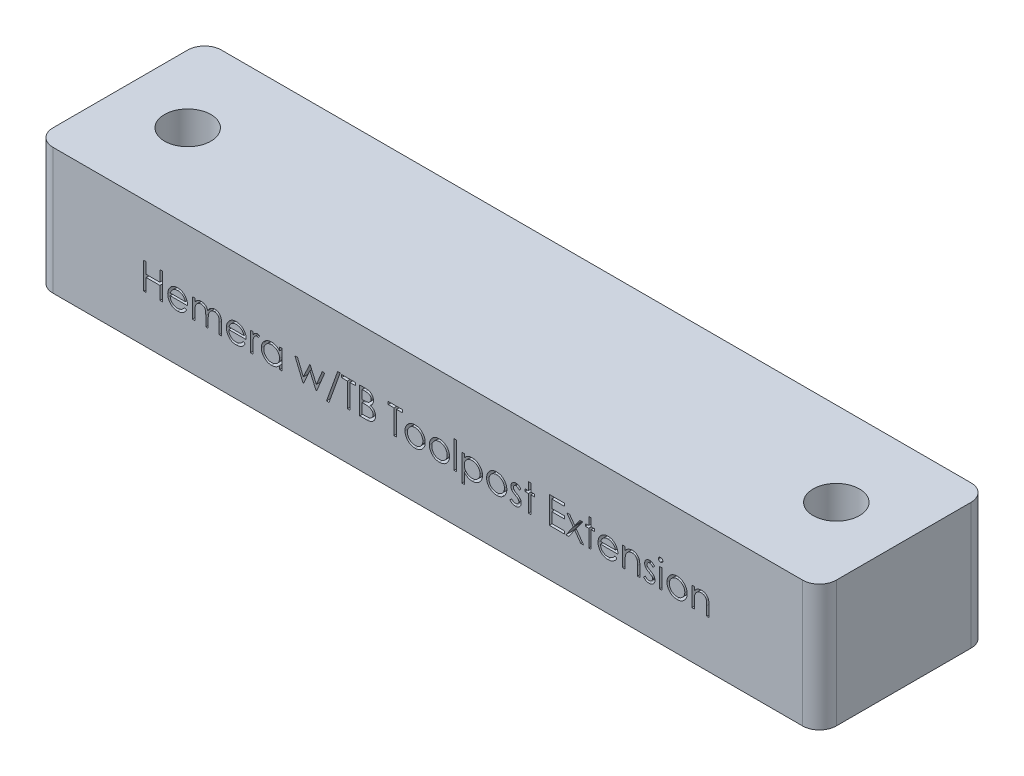
SolidWorks part; units mm, degrees
ref_plane "Front Plane" through (0, 0, 0) normal (0, 0, 1) x (1, 0, 0)
ref_plane "Top Plane" through (0, 0, 0) normal (0, 1, 0) x (1, 0, 0)
ref_plane "Right Plane" through (0, 0, 0) normal (1, 0, 0) x (0, 0, -1)
sketch "Sketch1" plane through (0, 0, 0) normal (0, 1, 0) x (1, 0, 0)
  line L0 (-44.5, -10) -> (44.5, -10)
  line L1 (46.5, -8) -> (46.5, 8)
  line L2 (44.5, 10) -> (-44.5, 10)
  line L3 (-46.5, 8) -> (-46.5, -8)
  arc A0 (44.5, -10) -> (46.5, -8) centre (44.5, -8) ccw
  arc A1 (46.5, 8) -> (44.5, 10) centre (44.5, 8) ccw
  arc A2 (-44.5, 10) -> (-46.5, 8) centre (-44.5, 8) ccw
  arc A3 (-46.5, -8) -> (-44.5, -10) centre (-44.5, -8) ccw
extrude "Boss-Extrude1" add sketch "Sketch1" along normal blind 15
hole_wizard "M5 Clearance Hole1" positions "Sketch2" profile "Sketch3" hole size "M5" standard "ANSI Metric" end condition through all
sketch "Sketch2" plane through (0, 15, 0) normal (0, 1, 0) x (1, 0, 0)
  line L0 (-44.5, -10) -> (44.5, -10) construction
  line L1 (46.5, -8) -> (46.5, 8) construction
  point P0 (38.5, 0)
  point P2 (-38.5, 0)
  dimension "D1" = 77
  dimension "D2" = 10
  dimension "D3" = 8
sketch "Sketch3" plane through (38.5, 15, 0) normal (1, 0, 0) x (0, 0, 1)
  line L0 (0, 0) -> (0, 15)
  line L1 (0, 15) -> (2.75, 15)
  line L2 (2.75, 15) -> (2.75, 0)
  line L5 (2.75, 0) -> (0, 0)
  line L11 (0, -6.35) -> (0, 107.95) construction
  dimension "Thru Hole Dia." = 5.5
  dimension "Thru Hole Depth" = 15
sketch "Sketch4" plane through (0, 0, 10) normal (0, 0, 1) x (1, 0, 0)
  line L0 (-34.1266, 5.5992) -> (33.994, 5.5992) construction
  text T0 "Hemera w/TB Toolpost Extension"
  point P3 (-0.0663, 5.5992)
extrude "Cut-Extrude1" cut sketch "Sketch4" against normal blind 1
